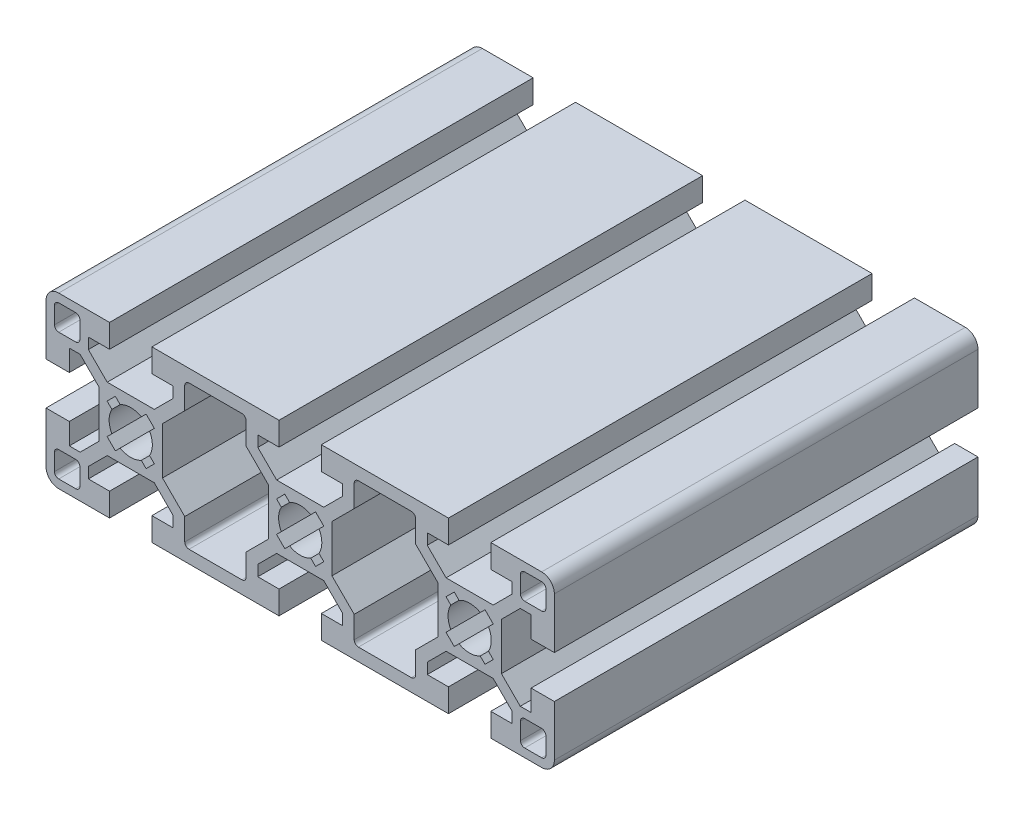
SolidWorks part; units mm, degrees
material "Aluminium"
ref_plane "Front Plane" through (0, 0, 0) normal (0, 0, 1) x (1, 0, 0)
ref_plane "Top Plane" through (0, 0, 0) normal (0, 1, 0) x (1, 0, 0)
ref_plane "Right Plane" through (0, 0, 0) normal (1, 0, 0) x (0, 0, -1)
sketch "Sketch1" plane through (0, 0, 0) normal (0, 0, 1) x (1, 0, 0)
  line L0 (-58, 13) -> (-58, 17)
  line L1 (-57, 18) -> (-53, 18)
  line L2 (-52, 17) -> (-52, 13)
  line L3 (-53, 12) -> (-57, 12)
  line L4 (-35.555, -2.5004) -> (-34.4237, -3.6318)
  line L5 (-34.4237, -3.6318) -> (-36.3682, -5.5763)
  line L6 (-36.3682, -5.5763) -> (-37.4996, -4.445)
  line L7 (-42.5004, -4.445) -> (-43.6318, -5.5763)
  line L8 (-43.6318, -5.5763) -> (-45.5763, -3.6318)
  line L9 (-45.5763, -3.6318) -> (-44.445, -2.5004)
  line L10 (-44.445, 2.5004) -> (-45.5763, 3.6318)
  line L11 (-45.5763, 3.6318) -> (-43.6318, 5.5763)
  line L12 (-43.6318, 5.5763) -> (-42.5004, 4.445)
  line L13 (-37.4996, 4.445) -> (-36.3682, 5.5763)
  line L14 (-36.3682, 5.5763) -> (-34.4237, 3.6318)
  line L15 (-34.4237, 3.6318) -> (-35.555, 2.5004)
  line L16 (-58, -17) -> (-58, -13)
  line L17 (-57, -12) -> (-53, -12)
  line L18 (-52, -13) -> (-52, -17)
  line L19 (-53, -18) -> (-57, -18)
  line L20 (-7.5, 5.5555) -> (-7.5, -5.5555)
  line L21 (-7.5, -5.5555) -> (-12.75, -10.8055)
  line L22 (-12.75, -10.8055) -> (-12.75, -16)
  line L23 (-13.75, -17) -> (-26.25, -17)
  line L24 (-27.25, -16) -> (-27.25, -10.8055)
  line L25 (-27.25, -10.8055) -> (-32.5, -5.5555)
  line L26 (-32.5, -5.5555) -> (-32.5, 5.5555)
  line L27 (-32.5, 5.5555) -> (-27.25, 10.8055)
  line L28 (-27.25, 10.8055) -> (-27.25, 16)
  line L29 (-26.25, 17) -> (-13.75, 17)
  line L30 (-12.75, 16) -> (-12.75, 10.8055)
  line L31 (-12.75, 10.8055) -> (-7.5, 5.5555)
  line L32 (7.5, -5.5555) -> (7.5, 5.5555)
  line L33 (7.5, 5.5555) -> (12.75, 10.8055)
  line L34 (12.75, 10.8055) -> (12.75, 16)
  line L35 (13.75, 17) -> (26.25, 17)
  line L36 (27.25, 16) -> (27.25, 10.8055)
  line L37 (27.25, 10.8055) -> (32.5, 5.5555)
  line L38 (32.5, 5.5555) -> (32.5, -5.5555)
  line L39 (32.5, -5.5555) -> (27.25, -10.8055)
  line L40 (27.25, -10.8055) -> (27.25, -16)
  line L41 (26.25, -17) -> (13.75, -17)
  line L42 (12.75, -16) -> (12.75, -10.8055)
  line L43 (12.75, -10.8055) -> (7.5, -5.5555)
  line L44 (58, -13) -> (58, -17)
  line L45 (57, -18) -> (53, -18)
  line L46 (52, -17) -> (52, -13)
  line L47 (53, -12) -> (57, -12)
  line L48 (35.555, 2.5004) -> (34.4237, 3.6318)
  line L49 (34.4237, 3.6318) -> (36.3682, 5.5763)
  line L50 (36.3682, 5.5763) -> (37.4996, 4.445)
  line L51 (42.5004, 4.445) -> (43.6318, 5.5763)
  line L52 (43.6318, 5.5763) -> (45.5763, 3.6318)
  line L53 (45.5763, 3.6318) -> (44.445, 2.5004)
  line L54 (44.445, -2.5004) -> (45.5763, -3.6318)
  line L55 (45.5763, -3.6318) -> (43.6318, -5.5763)
  line L56 (43.6318, -5.5763) -> (42.5004, -4.445)
  line L57 (37.4996, -4.445) -> (36.3682, -5.5763)
  line L58 (36.3682, -5.5763) -> (34.4237, -3.6318)
  line L59 (34.4237, -3.6318) -> (35.555, -2.5004)
  line L60 (58, 17) -> (58, 13)
  line L61 (57, 12) -> (53, 12)
  line L62 (52, 13) -> (52, 17)
  line L63 (53, 18) -> (57, 18)
  line L64 (-2.5004, -4.445) -> (-3.6318, -5.5763)
  line L65 (-3.6318, -5.5763) -> (-5.5763, -3.6318)
  line L66 (-5.5763, -3.6318) -> (-4.445, -2.5004)
  line L67 (-4.445, 2.5004) -> (-5.5763, 3.6318)
  line L68 (-5.5763, 3.6318) -> (-3.6318, 5.5763)
  line L69 (-3.6318, 5.5763) -> (-2.5004, 4.445)
  line L70 (2.5004, 4.445) -> (3.6318, 5.5763)
  line L71 (3.6318, 5.5763) -> (5.5763, 3.6318)
  line L72 (5.5763, 3.6318) -> (4.445, 2.5004)
  line L73 (4.445, -2.5004) -> (5.5763, -3.6318)
  line L74 (5.5763, -3.6318) -> (3.6318, -5.5763)
  line L75 (3.6318, -5.5763) -> (2.5004, -4.445)
  line L76 (-5.5555, -7.5) -> (5.5555, -7.5)
  line L77 (5.5555, -7.5) -> (10, -11.9445)
  line L78 (10, -11.9445) -> (10, -14.5)
  line L79 (10, -14.5) -> (5, -14.5)
  line L80 (5, -14.5) -> (5, -20)
  line L81 (5, -20) -> (35, -20)
  line L82 (35, -20) -> (35, -14.5)
  line L83 (35, -14.5) -> (30, -14.5)
  line L84 (30, -14.5) -> (30, -11.9445)
  line L85 (30, -11.9445) -> (34.4445, -7.5)
  line L86 (34.4445, -7.5) -> (45.5555, -7.5)
  line L87 (45.5555, -7.5) -> (50, -11.9445)
  line L88 (50, -11.9445) -> (50, -14.5)
  line L89 (50, -14.5) -> (45, -14.5)
  line L90 (45, -14.5) -> (45, -20)
  line L91 (45, -20) -> (57, -20)
  line L92 (60, -17) -> (60, -5)
  line L93 (60, -5) -> (54.5, -5)
  line L94 (54.5, -5) -> (54.5, -10)
  line L95 (54.5, -10) -> (51.9445, -10)
  line L96 (51.9445, -10) -> (47.5, -5.5555)
  line L97 (47.5, -5.5555) -> (47.5, 5.5555)
  line L98 (47.5, 5.5555) -> (51.9445, 10)
  line L99 (51.9445, 10) -> (54.5, 10)
  line L100 (54.5, 10) -> (54.5, 5)
  line L101 (54.5, 5) -> (60, 5)
  line L102 (60, 5) -> (60, 17)
  line L103 (57, 20) -> (45, 20)
  line L104 (45, 20) -> (45, 14.5)
  line L105 (45, 14.5) -> (50, 14.5)
  line L106 (50, 14.5) -> (50, 11.9445)
  line L107 (50, 11.9445) -> (45.5555, 7.5)
  line L108 (45.5555, 7.5) -> (34.4445, 7.5)
  line L109 (34.4445, 7.5) -> (30, 11.9445)
  line L110 (30, 11.9445) -> (30, 14.5)
  line L111 (30, 14.5) -> (35, 14.5)
  line L112 (35, 14.5) -> (35, 20)
  line L113 (35, 20) -> (5, 20)
  line L114 (5, 20) -> (5, 14.5)
  line L115 (5, 14.5) -> (10, 14.5)
  line L116 (10, 14.5) -> (10, 11.9445)
  line L117 (10, 11.9445) -> (5.5555, 7.5)
  line L118 (5.5555, 7.5) -> (-5.5555, 7.5)
  line L119 (-5.5555, 7.5) -> (-10, 11.9445)
  line L120 (-10, 11.9445) -> (-10, 14.5)
  line L121 (-10, 14.5) -> (-5, 14.5)
  line L122 (-5, 14.5) -> (-5, 20)
  line L123 (-5, 20) -> (-35, 20)
  line L124 (-35, 20) -> (-35, 14.5)
  line L125 (-35, 14.5) -> (-30, 14.5)
  line L126 (-30, 14.5) -> (-30, 11.9445)
  line L127 (-30, 11.9445) -> (-34.4445, 7.5)
  line L128 (-34.4445, 7.5) -> (-45.5555, 7.5)
  line L129 (-45.5555, 7.5) -> (-50, 11.9445)
  line L130 (-50, 11.9445) -> (-50, 14.5)
  line L131 (-50, 14.5) -> (-45, 14.5)
  line L132 (-45, 14.5) -> (-45, 20)
  line L133 (-45, 20) -> (-57, 20)
  line L134 (-60, 17) -> (-60, 5)
  line L135 (-60, 5) -> (-54.5, 5)
  line L136 (-54.5, 5) -> (-54.5, 10)
  line L137 (-54.5, 10) -> (-51.9445, 10)
  line L138 (-51.9445, 10) -> (-47.5, 5.5555)
  line L139 (-47.5, 5.5555) -> (-47.5, -5.5555)
  line L140 (-47.5, -5.5555) -> (-51.9445, -10)
  line L141 (-51.9445, -10) -> (-54.5, -10)
  line L142 (-54.5, -10) -> (-54.5, -5)
  line L143 (-54.5, -5) -> (-60, -5)
  line L144 (-60, -5) -> (-60, -17)
  line L145 (-57, -20) -> (-45, -20)
  line L146 (-45, -20) -> (-45, -14.5)
  line L147 (-45, -14.5) -> (-50, -14.5)
  line L148 (-50, -14.5) -> (-50, -11.9445)
  line L149 (-50, -11.9445) -> (-45.5555, -7.5)
  line L150 (-45.5555, -7.5) -> (-34.4445, -7.5)
  line L151 (-34.4445, -7.5) -> (-30, -11.9445)
  line L152 (-30, -11.9445) -> (-30, -14.5)
  line L153 (-30, -14.5) -> (-35, -14.5)
  line L154 (-35, -14.5) -> (-35, -20)
  line L155 (-35, -20) -> (-5, -20)
  line L156 (-5, -20) -> (-5, -14.5)
  line L157 (-5, -14.5) -> (-10, -14.5)
  line L158 (-10, -14.5) -> (-10, -11.9445)
  line L159 (-10, -11.9445) -> (-5.5555, -7.5)
  arc A0 (-58, 17) -> (-57, 18) centre (-57, 17) cw
  arc A1 (-53, 18) -> (-52, 17) centre (-53, 17) cw
  arc A2 (-52, 13) -> (-53, 12) centre (-53, 13) cw
  arc A3 (-57, 12) -> (-58, 13) centre (-57, 13) cw
  arc A4 (-35.555, 2.5004) -> (-35.555, -2.5004) centre (-40, 0) cw
  arc A5 (-37.4996, -4.445) -> (-42.5004, -4.445) centre (-40, 0) cw
  arc A6 (-44.445, -2.5004) -> (-44.445, 2.5004) centre (-40, 0) cw
  arc A7 (-42.5004, 4.445) -> (-37.4996, 4.445) centre (-40, 0) cw
  arc A8 (-58, -13) -> (-57, -12) centre (-57, -13) cw
  arc A9 (-53, -12) -> (-52, -13) centre (-53, -13) cw
  arc A10 (-52, -17) -> (-53, -18) centre (-53, -17) cw
  arc A11 (-57, -18) -> (-58, -17) centre (-57, -17) cw
  arc A12 (-12.75, -16) -> (-13.75, -17) centre (-13.75, -16) cw
  arc A13 (-26.25, -17) -> (-27.25, -16) centre (-26.25, -16) cw
  arc A14 (-27.25, 16) -> (-26.25, 17) centre (-26.25, 16) cw
  arc A15 (-13.75, 17) -> (-12.75, 16) centre (-13.75, 16) cw
  arc A16 (12.75, 16) -> (13.75, 17) centre (13.75, 16) cw
  arc A17 (26.25, 17) -> (27.25, 16) centre (26.25, 16) cw
  arc A18 (27.25, -16) -> (26.25, -17) centre (26.25, -16) cw
  arc A19 (13.75, -17) -> (12.75, -16) centre (13.75, -16) cw
  arc A20 (58, -17) -> (57, -18) centre (57, -17) cw
  arc A21 (53, -18) -> (52, -17) centre (53, -17) cw
  arc A22 (52, -13) -> (53, -12) centre (53, -13) cw
  arc A23 (57, -12) -> (58, -13) centre (57, -13) cw
  arc A24 (35.555, -2.5004) -> (35.555, 2.5004) centre (40, 0) cw
  arc A25 (37.4996, 4.445) -> (42.5004, 4.445) centre (40, 0) cw
  arc A26 (44.445, 2.5004) -> (44.445, -2.5004) centre (40, 0) cw
  arc A27 (42.5004, -4.445) -> (37.4996, -4.445) centre (40, 0) cw
  arc A28 (58, 13) -> (57, 12) centre (57, 13) cw
  arc A29 (53, 12) -> (52, 13) centre (53, 13) cw
  arc A30 (52, 17) -> (53, 18) centre (53, 17) cw
  arc A31 (57, 18) -> (58, 17) centre (57, 17) cw
  arc A32 (2.5004, -4.445) -> (-2.5004, -4.445) centre (0, 0) cw
  arc A33 (-4.445, -2.5004) -> (-4.445, 2.5004) centre (0, 0) cw
  arc A34 (-2.5004, 4.445) -> (2.5004, 4.445) centre (0, 0) cw
  arc A35 (4.445, 2.5004) -> (4.445, -2.5004) centre (0, 0) cw
  arc A36 (57, -20) -> (60, -17) centre (57, -17) ccw
  arc A37 (60, 17) -> (57, 20) centre (57, 17) ccw
  arc A38 (-57, 20) -> (-60, 17) centre (-57, 17) ccw
  arc A39 (-60, -17) -> (-57, -20) centre (-57, -17) ccw
extrude "Boss-Extrude1" add sketch "Sketch1" against normal mid plane 100
